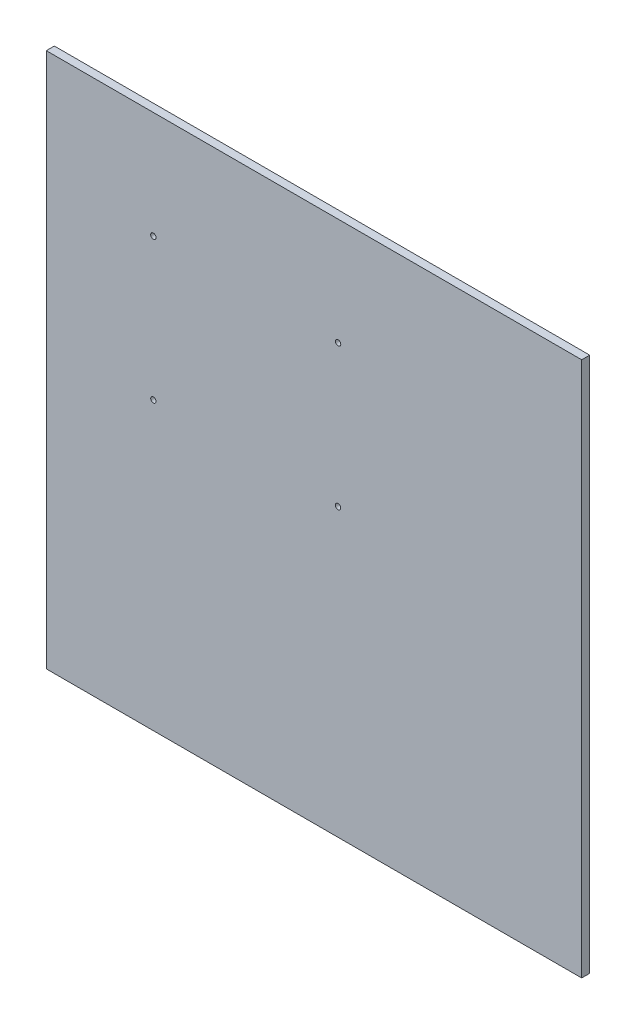
SolidWorks part; units mm, degrees
ref_plane "Přední rovina" through (0, 0, 0) normal (0, 0, 1) x (1, 0, 0)
ref_plane "Horní rovina" through (0, 0, 0) normal (0, 1, 0) x (1, 0, 0)
ref_plane "Pravá rovina" through (0, 0, 0) normal (1, 0, 0) x (0, 0, -1)
sketch "Skica1" plane through (0, 0, 0) normal (0, 0, 1) x (1, 0, 0)
  line L1 (0, 0) -> (200, 0)
  line L2 (0, 0) -> (0, 200)
  line L3 (0, 200) -> (200, 200)
  line L4 (200, 0) -> (200, 200)
  dimension "D1" = 200
  dimension "D2" = 200
extrude "Přidat vysunutím1" add sketch "Skica1" along normal blind 3
sketch "Skica2" plane through (0, 0, 3) normal (0, 0, 1) x (1, 0, 0)
  line L0 (0, 200) -> (0, 0) construction
  line L1 (200, 200) -> (0, 200) construction
  line L2 (40, 160) -> (109, 160) construction
  circle A0 centre (40, 160) radius 1
  circle A1 centre (109, 160) radius 1
  circle A2 centre (109, 107) radius 1
  circle A3 centre (40, 107) radius 1
  dimension "D1" = 2
  dimension "D2" = 40
  dimension "D3" = 40
  dimension "D7" = 53
  dimension "D6" = 69
  dimension "D4" = 2
  dimension "D5" = 2
extrude "Odebrat vysunutím1" cut sketch "Skica2" against normal blind 2
